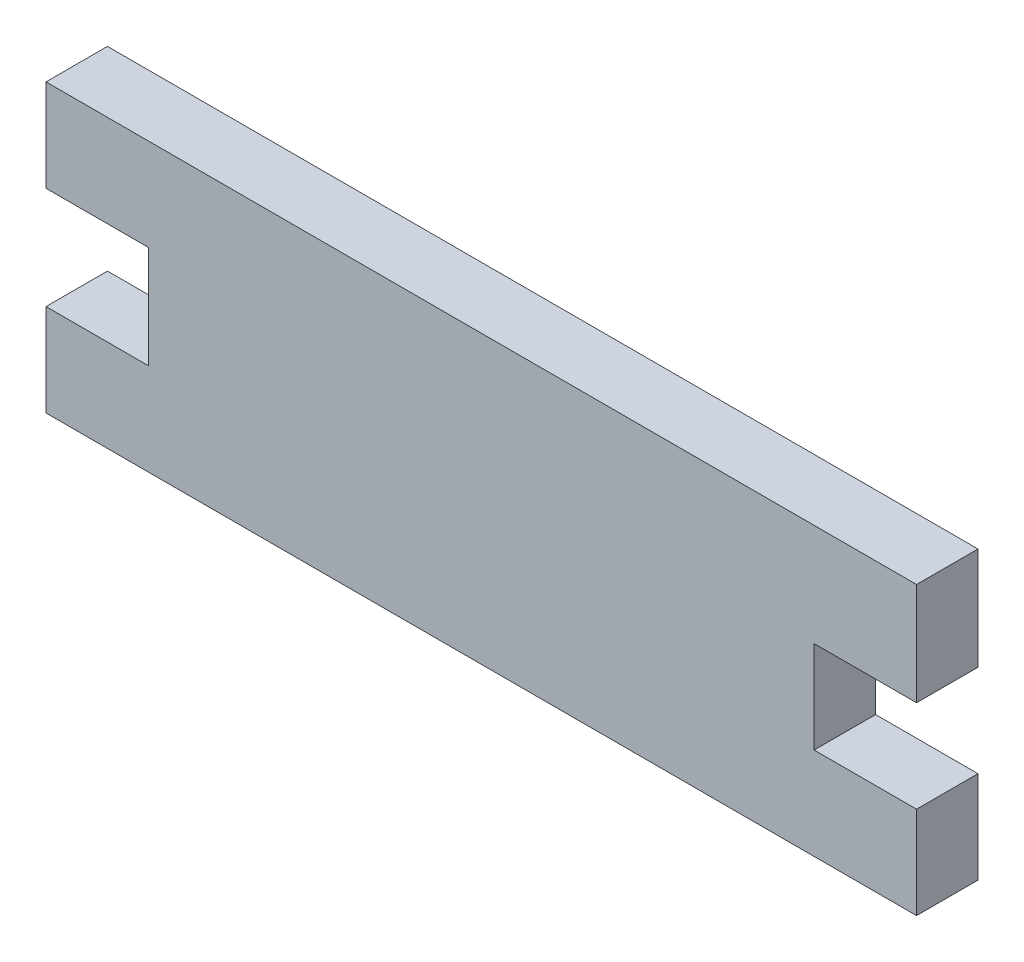
SolidWorks part; units mm, degrees
ref_plane "Plan de face" through (0, 0, 0) normal (0, 0, 1) x (1, 0, 0)
ref_plane "Plan de dessus" through (0, 0, 0) normal (0, 1, 0) x (1, 0, 0)
ref_plane "Plan de droite" through (0, 0, 0) normal (1, 0, 0) x (0, 0, -1)
sketch "Esquisse1" plane through (0, 0, 0) normal (0, 0, 1) x (1, 0, 0)
  line L0 (-11.5096, 2.6636) -> (-11.5096, -2.3364) construction
  line L1 (-16.5096, 7.1636) -> (25.9904, 7.1636)
  line L2 (-16.5096, 7.1636) -> (-16.5096, 2.6636)
  line L3 (-16.5096, -6.8364) -> (25.9904, -6.8364)
  line L4 (25.9904, 7.1636) -> (25.9904, 2.1636)
  line L13 (20.9904, 2.1636) -> (20.9904, -2.3364) construction
  line L14 (-16.5096, -2.3364) -> (-16.5096, -6.8364)
  line L15 (-16.5096, 2.6636) -> (-11.5096, 2.6636)
  line L17 (-16.5096, -2.3364) -> (-11.5096, -2.3364)
  line L18 (-11.5096, 2.6636) -> (-11.5096, -2.3364)
  line L19 (25.9904, 2.1636) -> (20.9904, 2.1636)
  line L21 (25.9904, -2.3364) -> (20.9904, -2.3364)
  line L22 (20.9904, 2.1636) -> (20.9904, -2.3364)
  line L23 (25.9904, -2.3364) -> (25.9904, -6.8364)
  point P16 (-14.0096, 2.6636)
  dimension "D1" = 42.5
  dimension "D2" = 14
  dimension "D3" = 5
  dimension "D4" = 5
  dimension "D7" = 5
  dimension "D8" = 4.5
extrude "Boss.-Extru.1" add sketch "Esquisse1" along normal blind 3
